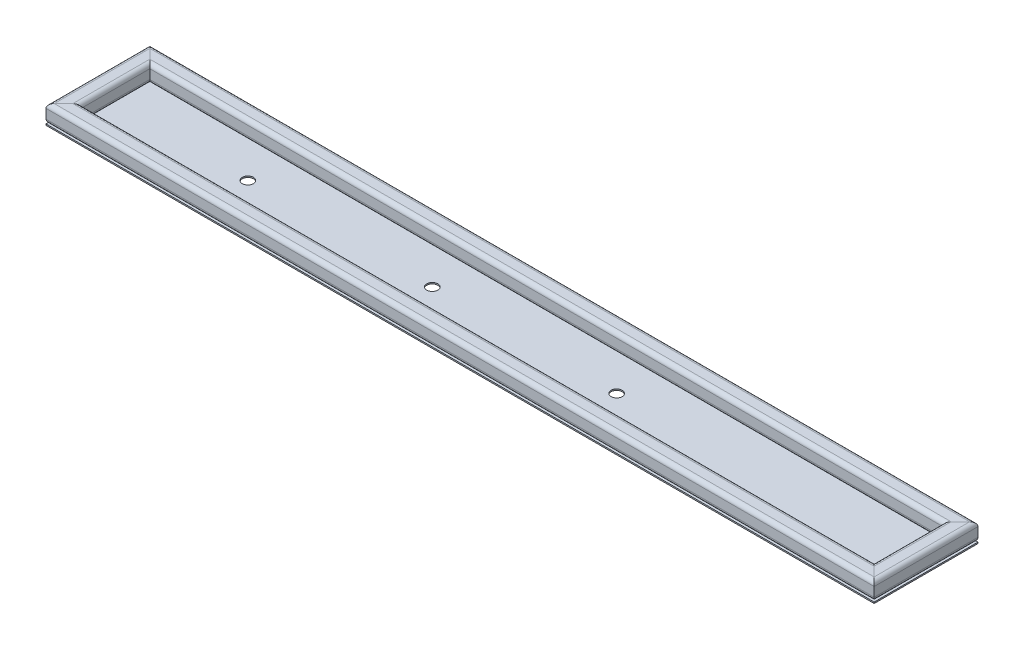
SolidWorks part; units mm, degrees
ref_plane "Alzado" through (0, 0, 0) normal (0, 0, 1) x (1, 0, 0)
ref_plane "Planta" through (0, 0, 0) normal (0, 1, 0) x (1, 0, 0)
ref_plane "Vista lateral" through (0, 0, 0) normal (1, 0, 0) x (0, 0, -1)
sketch "Croquis1" plane through (0, 0, 0) normal (0, 1, 0) x (1, 0, 0)
  line L1 (-598.2, 75) -> (598.2, 75)
  line L2 (-598.2, 75) -> (-598.2, -75)
  line L3 (-598.2, -75) -> (598.2, -75)
  line L4 (598.2, 75) -> (598.2, -75)
  line L5 (-598.2, 75) -> (598.2, -75) construction
  line L6 (-598.2, -75) -> (598.2, 75) construction
  point P0 (0, 0)
  dimension "D1" = 150
  dimension "D2" = 1196.4
other "Tubo cuadrado 2 X 2 X 0.25(1)"
ref_plane "Plano1" through (-585.5, 12.7, -75) normal (0, 0, 1) x (1, 0, 0)
sketch "Sketch1" plane through (-585.5, 12.7, -75) normal (0, 0, 1) x (1, 0, 0)
  line L0 (-6.7, -9.7) -> (6.7, -9.7)
  line L1 (-9.7, -6.7) -> (-9.7, 6.7)
  line L2 (6.7, 9.7) -> (-6.7, 9.7)
  line L3 (9.7, 6.7) -> (9.7, -6.7)
  line L4 (-6.7, -12.7) -> (6.7, -12.7)
  line L5 (-12.7, -6.7) -> (-12.7, 6.7)
  line L6 (6.7, 12.7) -> (-6.7, 12.7)
  line L7 (12.7, 6.7) -> (12.7, -6.7)
  line L8 (0, 0) -> (9.7, 0) construction
  line L9 (0, 0) -> (0, 9.7) construction
  arc A0 (12.7, 6.7) -> (6.7, 12.7) centre (6.7, 6.7) ccw
  arc A1 (6.7, -12.7) -> (12.7, -6.7) centre (6.7, -6.7) ccw
  arc A2 (-12.7, -6.7) -> (-6.7, -12.7) centre (-6.7, -6.7) ccw
  arc A3 (-6.7, 12.7) -> (-12.7, 6.7) centre (-6.7, 6.7) ccw
  arc A4 (-6.7, 9.7) -> (-9.7, 6.7) centre (-6.7, 6.7) ccw
  arc A5 (9.7, 6.7) -> (6.7, 9.7) centre (6.7, 6.7) ccw
  arc A6 (6.7, -9.7) -> (9.7, -6.7) centre (6.7, -6.7) ccw
  arc A7 (-9.7, -6.7) -> (-6.7, -9.7) centre (-6.7, -6.7) ccw
  point P3 (0, 12.7)
  point P4 (12.7, 0)
  point P5 (0, -12.7)
  point P6 (-12.7, 0)
  point P7 (-12.7, 12.7)
  point P8 (-12.7, -12.7)
  point P33 (0, 0)
  point P35 (12.7, -12.7)
  point P36 (12.7, 12.7)
  point P37 (0, 0)
  dimension "D1" = 6
  dimension "Thickness" = 3
  dimension "V_leg" = 25.4
sketch "Croquis3" plane through (0, 0, 0) normal (0, -1, 0) x (1, 0, 0)
  line L1 (598.2, 75) -> (-598.2, 75)
  line L2 (598.2, 75) -> (598.2, -75)
  line L3 (598.2, -75) -> (-598.2, -75)
  line L4 (-598.2, 75) -> (-598.2, -75)
  line L5 (598.2, 75) -> (-598.2, -75) construction
  line L6 (598.2, -75) -> (-598.2, 75) construction
  point P0 (0, 0)
extrude "Saliente-Extruir1" add sketch "Croquis3" along normal blind 1.9 separate body
ref_plane "Plano2" through (0, 0, 0) normal (0, 0, 1) x (1, 0, 0)
sketch "Croquis4" plane through (0, 0, 0) normal (0, 1, 0) x (1, 0, 0)
  circle A0 centre (-268.2099, 0) radius 7.9375
  circle A1 centre (-291.2099, 0.2449) radius 3.175
  circle A2 centre (-245.2099, -0.2449) radius 3.175
  circle A3 centre (-58.2099, 0) radius 7.9375
  circle A4 centre (-81.2099, 0.2449) radius 3.175
  circle A5 centre (-35.2099, -0.2449) radius 3.175
  circle A6 centre (151.7851, 0) radius 7.9375
  circle A7 centre (174.7851, -0.2449) radius 3.175
  circle A8 centre (128.7851, 0.2449) radius 3.175
sketch "Croquis5" plane through (0, 0, 0) normal (0, 1, 0) x (1, 0, 0)
  line L0 (155.7336, -1.5354) -> (151.2228, 0) construction
  line L1 (151.2228, 0) -> (-115.175, 0) construction
  line L2 (-115.175, 0) -> (-381.5729, 0) construction
  circle A0 centre (151.2228, 0) radius 8
  circle A1 centre (-115.175, 0) radius 8
  circle A2 centre (-381.5729, 0) radius 8
  dimension "D1" = 16
  dimension "D2" = 16
  dimension "D3" = 16
extrude "Cortar-Extruir1" cut sketch "Croquis5" against normal blind 10
